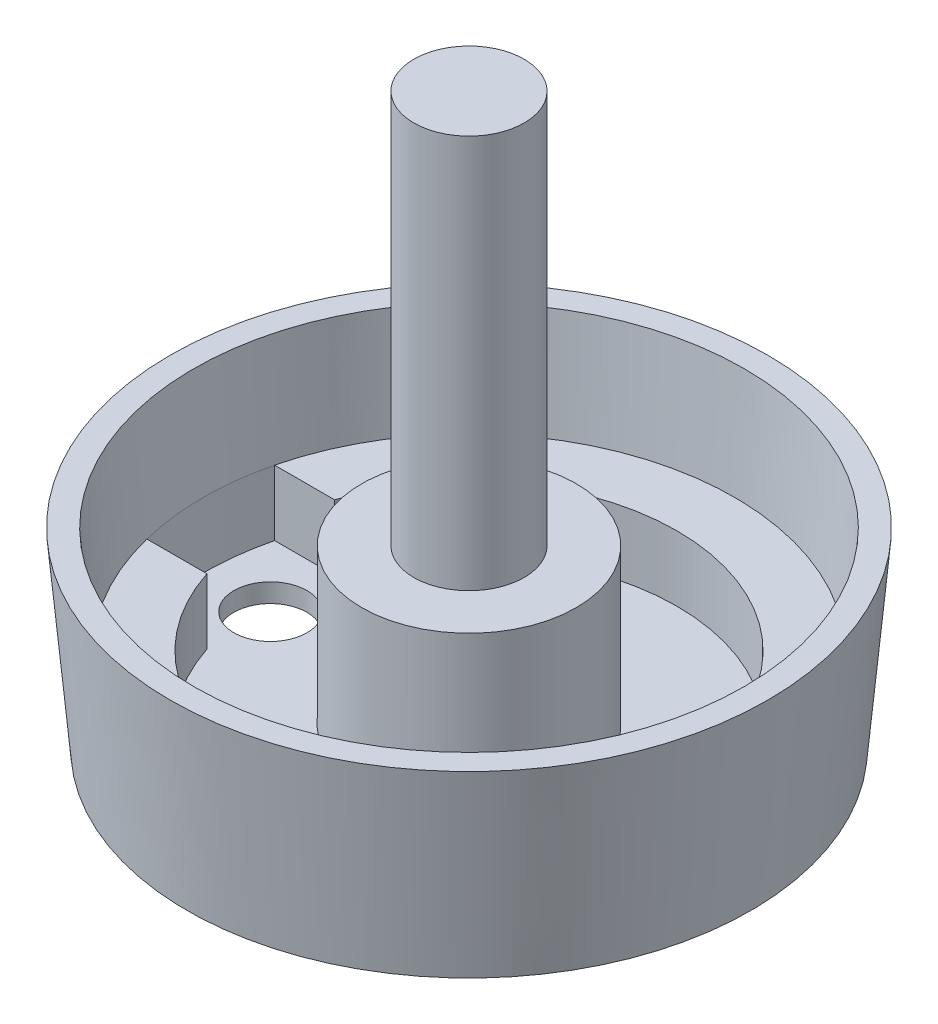
SolidWorks part; units mm, degrees
ref_plane "Front Plane" through (0, 0, 0) normal (0, 0, 1) x (1, 0, 0)
ref_plane "Top Plane" through (0, 0, 0) normal (0, 1, 0) x (1, 0, 0)
ref_plane "Right Plane" through (0, 0, 0) normal (1, 0, 0) x (0, 0, -1)
sketch "Sketch1" plane through (0, 0, 0) normal (0, 0, 1) x (1, 0, 0)
  line L0 (-46.101, 0) -> (46.101, 0) construction
  line L1 (0, 0) -> (-46.101, 0)
  line L2 (-46.101, 0) -> (-48.895, 31.242)
  line L3 (-48.895, 31.242) -> (-45.0572, 31.242)
  line L4 (-45.0572, 31.242) -> (-43.4955, 13.7795)
  line L5 (0, 0) -> (0, 103.3728) construction
  line L6 (-43.4955, 13.7795) -> (0, 13.7795)
  line L7 (0, 13.7795) -> (0, 0)
  point P4 (0, 0)
  dimension "D1" = 48.895
  dimension "D2" = 46.101
  dimension "D3" = 17.4625
  dimension "D4" = 31.242
revolve "Revolve1" add sketch "Sketch1" angle 360 about L5
sketch "Sketch2" plane through (0, 0, 0) normal (0, -1, 0) x (1, 0, 0)
  circle A0 centre (16.891, 0) radius 3.175
  circle A4 centre (-32.4993, 0) radius 5.9817
  dimension "D1" = 6.35
  dimension "D2" = 16.891
  dimension "D3" = 11.9634
  dimension "D4" = 32.4993
extrude "Cut-Extrude1" cut sketch "Sketch2" against normal through all
sketch "Sketch4" plane through (0, 13.7795, 0) normal (0, 1, 0) x (1, 0, 0)
  line L0 (0, 0) -> (0, 30.4761) construction
  line L1 (0, 30.4761) -> (0, 0) construction
  line L2 (0, 0) -> (-32.4993, 0) construction
  line L3 (-32.3729, -10.5093) -> (-42.2068, -10.5093)
  line L4 (-32.4037, 10.414) -> (-42.2304, 10.414)
  arc A0 (-32.3729, -10.5093) -> (-32.4037, 10.414) centre (0, 0) ccw
  circle A1 centre (0, 0) radius 43.4955 construction
  arc A2 (-42.2304, 10.414) -> (-42.2068, -10.5093) centre (0, 0) ccw
  dimension "D1" = 68.072
  dimension "D2" = 10.5092
  dimension "D3" = 10.414
extrude "Cut-Extrude3" cut sketch "Sketch4" against normal blind 10.6934
sketch "Sketch5" plane through (0, 0, 0) normal (0, -1, 0) x (1, 0, 0)
  line L1 (-9.652, 18.9039) -> (9.652, 18.9039)
  line L2 (-9.652, 18.9039) -> (-9.652, -18.904)
  line L3 (-9.652, -18.904) -> (9.652, -18.904)
  line L4 (9.652, 18.9039) -> (9.652, -18.904)
  line L5 (-9.652, 18.9039) -> (9.652, -18.904) construction
  line L6 (-9.652, -18.904) -> (9.652, 18.9039) construction
  point P0 (0, 0)
  dimension "D1" = 37.8079
  dimension "D2" = 19.304
extrude "Boss-Extrude1" add sketch "Sketch5" along normal blind 12.4587
sketch "Sketch6" plane through (0, 3.0861, 0) normal (0, 1, 0) x (1, 0, 0)
  circle A0 centre (0, 0) radius 17.5641
  dimension "D1" = 35.1282
extrude "Boss-Extrude2" add sketch "Sketch6" along normal blind 25.6032
sketch "Sketch7" plane through (0, 28.6893, 0) normal (0, 1, 0) x (1, 0, 0)
  circle A0 centre (0, 0) radius 9.036
  dimension "D1" = 18.0721
extrude "Boss-Extrude3" add sketch "Sketch7" along normal blind 64.4271
sketch "Sketch8" plane through (0, -12.4587, 0) normal (0, -1, 0) x (1, 0, 0)
  point P0 (0, 0)
sketch "Sketch3" plane through (0, 3.0861, 0) normal (0, 1, 0) x (1, 0, 0)
  line L0 (16.891, 6.4158) -> (16.891, -6.4158) construction
  line L1 (22.4472, -3.2079) -> (22.4472, 3.2079)
  line L2 (22.4472, 3.2079) -> (16.891, 6.4158)
  line L3 (16.891, 6.4158) -> (11.3347, 3.2079)
  line L4 (11.3347, 3.2079) -> (11.3347, -3.2079)
  line L5 (11.3347, -3.2079) -> (16.891, -6.4158)
  line L6 (16.891, -6.4158) -> (22.4472, -3.2079)
  circle A0 centre (16.891, 0) radius 5.5562 construction
  dimension "D1" = 11.1125
extrude "Cut-Extrude2" cut sketch "Sketch3" against normal blind 1.524
